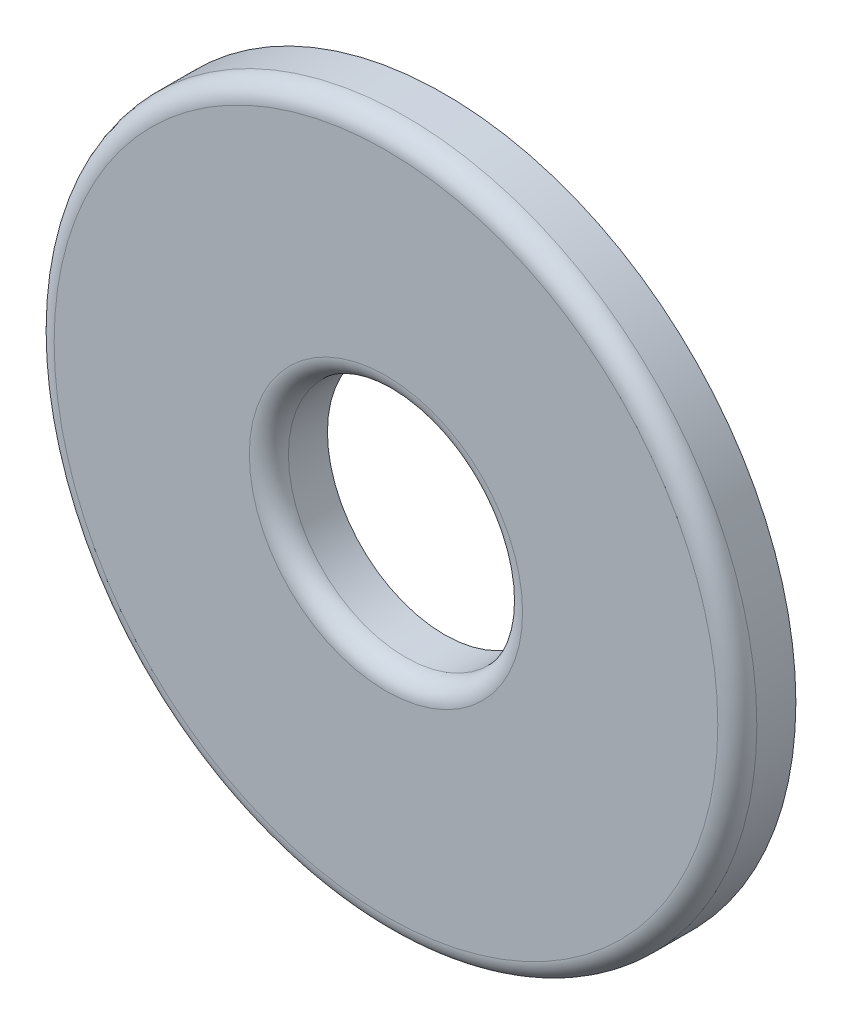
SolidWorks part; units mm, degrees
ref_plane "Front Plane" through (0, 0, 0) normal (0, 0, 1) x (1, 0, 0)
ref_plane "Top Plane" through (0, 0, 0) normal (0, 1, 0) x (1, 0, 0)
ref_plane "Right Plane" through (0, 0, 0) normal (1, 0, 0) x (0, 0, -1)
sketch "Sketch1" plane through (0, 0, 0) normal (0, 0, 1) x (1, 0, 0)
  circle A0 centre (0, 0) radius 4.5
  circle A1 centre (0, 0) radius 1.5
  dimension "D1" = 9
  dimension "D2" = 3
extrude "Boss-Extrude1" add sketch "Sketch1" along normal blind 0.75
fillet "Fillet1" radius 0.25 2 edges at (1.5, 0, 0.75) (4.5, 0, 0.75)
